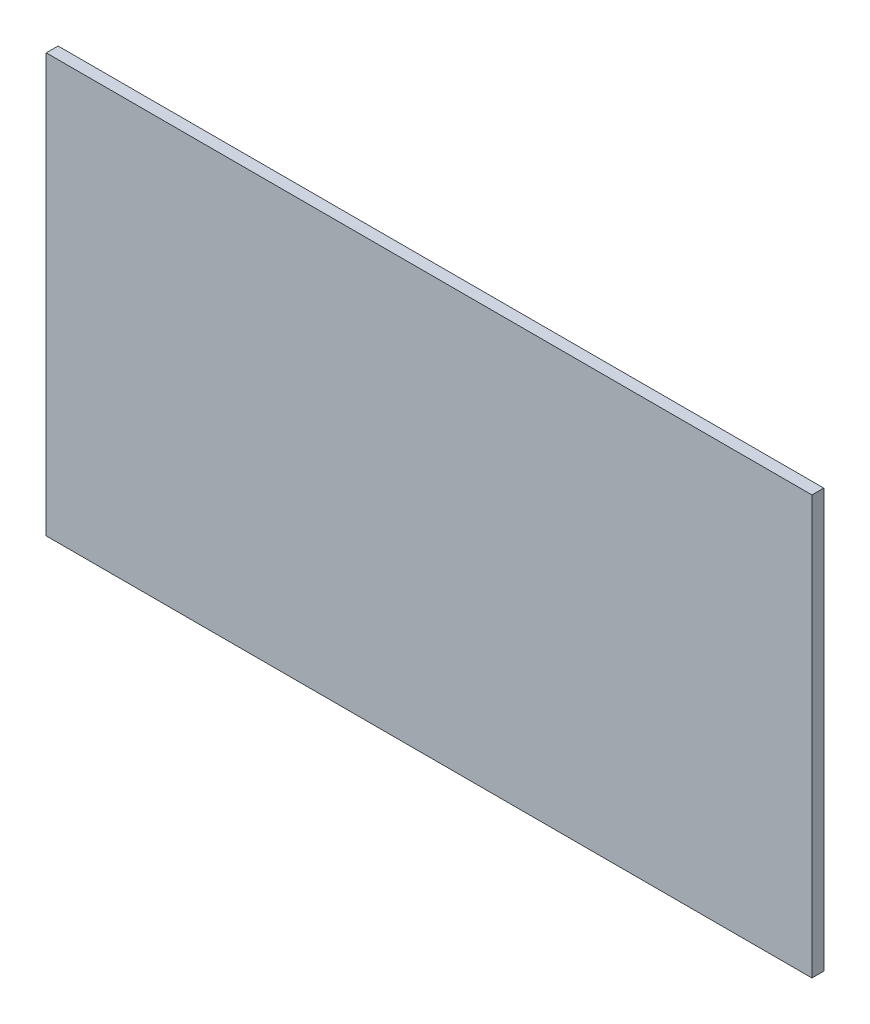
SolidWorks part; units mm, degrees
ref_plane "Front Plane" through (0, 0, 0) normal (0, 0, 1) x (1, 0, 0)
ref_plane "Top Plane" through (0, 0, 0) normal (0, 1, 0) x (1, 0, 0)
ref_plane "Right Plane" through (0, 0, 0) normal (1, 0, 0) x (0, 0, -1)
sketch "Sketch1" plane through (0, 0, 0) normal (0, 0, 1) x (1, 0, 0)
  line L1 (0, 0) -> (194, 0)
  line L2 (0, 0) -> (0, 106)
  line L3 (0, 106) -> (194, 106)
  line L4 (194, 0) -> (194, 106)
  dimension "D1" = 194
  dimension "D2" = 106
extrude "Profile" add sketch "Sketch1" along normal blind 3
equation "\"Profile_Depth\" = 3mm"
equation "\"D1@Profile\" = \"Profile_Depth\""
equation "\"Profile_Sketch_1\" = 194mm"
equation "\"D1@Sketch1\" = \"Profile_Sketch_1\""
equation "\"Profile_Sketch_2\" = 106mm"
equation "\"D2@Sketch1\" = \"Profile_Sketch_2\""
equation "\"EnvelopeWidth\" = 194mm"
equation "\"EnvelopeHeight\" = 106mm"
